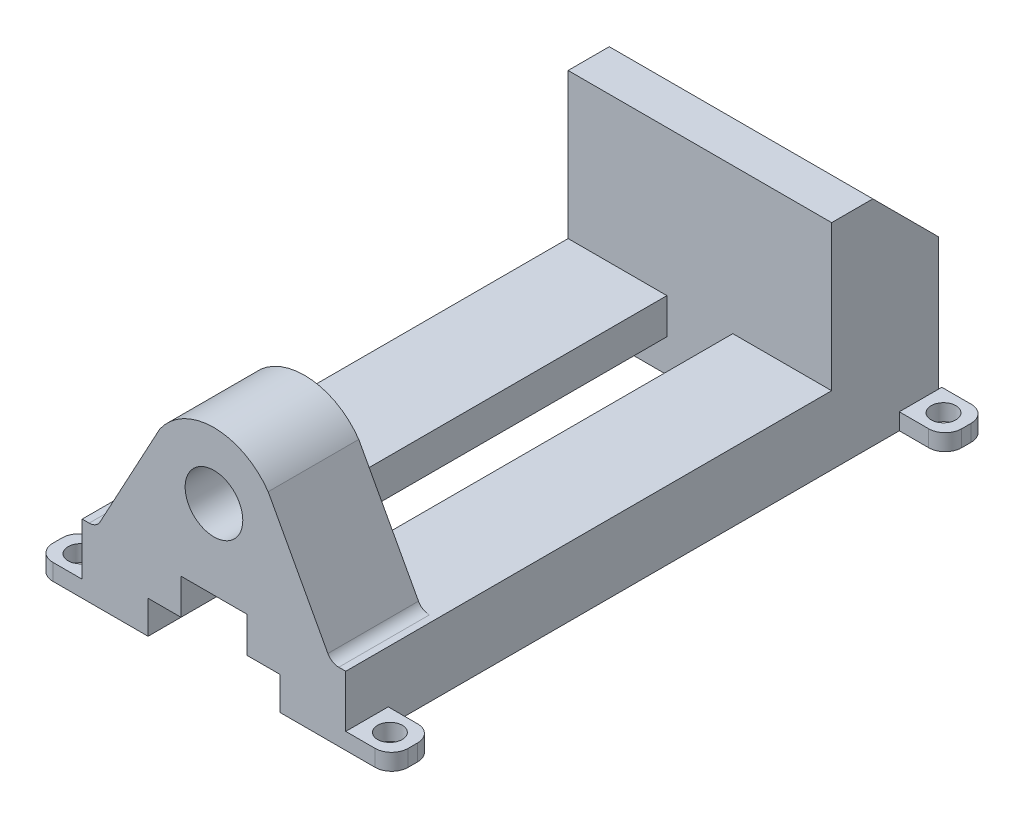
SolidWorks part; units mm, degrees
ref_plane "Front Plane" through (0, 0, 0) normal (0, 0, 1) x (1, 0, 0)
ref_plane "Top Plane" through (0, 0, 0) normal (0, 1, 0) x (1, 0, 0)
ref_plane "Right Plane" through (0, 0, 0) normal (1, 0, 0) x (0, 0, -1)
sketch "Sketch1" plane through (0, 0, 0) normal (0, 0, 1) x (1, 0, 0)
  line L0 (-31.5512, -18.1216) -> (32.4488, -18.1216)
  line L1 (-31.5512, -18.1216) -> (32.4488, -18.1216)
  line L2 (-31.5512, -18.1216) -> (-31.5512, -1.4716)
  line L3 (-31.5512, -1.4716) -> (-29.8548, -1.4716)
  line L4 (-27.2168, 0.0997) -> (-12.7169, 26.8735)
  line L5 (32.4488, -18.1216) -> (32.4488, -1.4716)
  line L6 (32.4488, -1.4716) -> (30.7525, -1.4716)
  line L7 (28.1145, 0.0997) -> (13.6146, 26.8735)
  arc A0 (15.2575, 23.8399) -> (-14.3598, 23.8399) centre (0.4488, 17.7816) ccw
  arc A1 (-29.8548, -1.4716) -> (-27.2168, 0.0997) centre (-29.8548, 1.5284) ccw
  arc A2 (30.7525, -1.4716) -> (28.1145, 0.0997) centre (30.7525, 1.5284) cw
  point P0 (0.4488, -0.17)
  point P1 (0.4488, -0.17)
  dimension "D3" = 3
  dimension "D1" = 64
  dimension "D2" = 16.65
extrude "Boss-Extrude1" add sketch "Sketch1" along normal blind 22 contours L6 A2 L7 A0 L4 A1 L3 L2 L0 L5
hole_wizard "M16 Tapped Hole1" positions "Sketch2" profile "Sketch3" tap size "M16" standard "ISO" end condition through all
sketch "Sketch2" plane through (0, 0, 22) normal (0, 0, 1) x (1, 0, 0)
  arc A0 (13.6146, 26.8735) -> (-12.7169, 26.8735) centre (0.4488, 17.7816) ccw construction
  point P0 (0.4488, 17.7816)
  dimension "D1" = 32
  dimension "D2" = 0
sketch "Sketch3" plane through (0.4488, 17.7816, 22) normal (1, 0, 0) x (0, -1, 0)
  line L0 (0, 0) -> (0, 22)
  line L1 (0, 22) -> (7, 22)
  line L2 (7, 22) -> (7, 0)
  line L5 (7, 0) -> (0, 0)
  line L11 (0, -6.35) -> (0, 107.95) construction
  dimension "Thru Tap Drill Dia." = 14
  dimension "Thru Tap Drill Depth" = 22
cosmetic thread "Hole Thread1" parameters "D2"=16
sketch "Sketch4" plane through (0, 0, 0) normal (0, 0, 1) x (1, 0, 0)
  line L1 (0.4488, -33.3057) -> (0.4488, 71.1608) construction
  line L7 (16.4488, -18.1216) -> (16.4488, -10.1216)
  line L8 (-31.5512, -18.1216) -> (32.4488, -18.1216) construction
  line L9 (16.4488, -10.1216) -> (8.4488, -10.1216)
  line L10 (8.4488, -10.1216) -> (8.4488, -1.4716)
  line L11 (8.4488, -1.4716) -> (32.4488, -1.4716)
  line L12 (32.4488, -18.1216) -> (32.4488, -1.4716) construction
  line L13 (32.4488, -1.4716) -> (32.4488, -18.1216)
  line L14 (32.4488, -18.1216) -> (16.4488, -18.1216)
  line L15 (-7.5512, -10.1216) -> (-7.5512, -1.4716)
  line L16 (-15.5512, -18.1216) -> (-15.5512, -10.1216)
  line L17 (-15.5512, -10.1216) -> (-7.5512, -10.1216)
  line L18 (-7.5512, -1.4716) -> (-31.5512, -1.4716)
  line L19 (-31.5512, -18.1216) -> (-15.5512, -18.1216)
  line L20 (-31.5512, -1.4716) -> (-31.5512, -18.1216)
  point P4 (0.4488, -18.1216)
  dimension "D1" = 16
  dimension "D2" = 16.65
  dimension "D3" = 8.65
  dimension "D4" = 8
extrude "Boss-Extrude2" add sketch "Sketch4" against normal blind 96
sketch "Sketch5" plane through (0, 0, 22) normal (0, 0, 1) x (1, 0, 0)
  line L9 (-15.5512, -18.1216) -> (16.4488, -18.1216)
  line L10 (-31.5512, -18.1216) -> (32.4488, -18.1216) construction
  line L11 (16.4488, -18.1216) -> (16.4488, -10.1216)
  line L12 (16.4488, -10.1216) -> (8.4488, -10.1216)
  line L13 (8.4488, -10.1216) -> (8.4488, -1.4716)
  line L14 (8.4488, -1.4716) -> (-7.5512, -1.4716)
  line L16 (-7.5512, -10.1216) -> (-7.5512, -1.4716)
  line L17 (-15.5512, -10.1216) -> (-7.5512, -10.1216)
  line L18 (-15.5512, -18.1216) -> (-15.5512, -10.1216)
  dimension "D2" = 8
  dimension "D3" = 8
  dimension "D4" = 8.65
extrude "Cut-Extrude1" cut sketch "Sketch5" against normal through all
sketch "Sketch8" plane through (0, 0, -96) normal (0, 0, -1) x (-1, 0, 0)
  line L1 (-32.4488, -18.1216) -> (31.5512, -18.1216)
  line L2 (-32.4488, -18.1216) -> (-32.4488, 33.8784)
  line L3 (-32.4488, 33.8784) -> (31.5512, 33.8784)
  line L4 (31.5512, -18.1216) -> (31.5512, 33.8784)
  dimension "D1" = 52
extrude "Boss-Extrude3" add sketch "Sketch8" along normal blind 26
chamfer "Chamfer1" distance 16 angle 45 1 edges at (0.4488, 33.8784, -122)
sketch "Sketch11" plane through (0, -18.1216, 0) normal (0, -1, 0) x (-1, 0, 0)
  line L1 (-32.4488, -22) -> (-39.5888, -22)
  line L2 (-32.4488, -22) -> (-32.4488, -11.68)
  line L3 (-32.4488, -11.68) -> (-39.5888, -11.68)
  line L4 (-43.5888, -18) -> (-43.5888, -15.68)
  line L5 (31.5512, -11.68) -> (38.6912, -11.68)
  line L6 (42.6912, -18) -> (42.6912, -15.68)
  line L7 (31.5512, -22) -> (38.6912, -22)
  line L8 (31.5512, -22) -> (31.5512, -11.68)
  line L9 (-32.4488, 112.435) -> (-39.5888, 112.435)
  line L10 (-43.5888, 118.755) -> (-43.5888, 116.435)
  line L11 (-32.4488, 122.755) -> (-39.5888, 122.755)
  line L12 (-32.4488, 122.755) -> (-32.4488, 112.435)
  line L13 (31.5512, 122.755) -> (31.5512, 112.435)
  line L14 (31.5512, 122.755) -> (38.6912, 122.755)
  line L15 (42.6912, 118.755) -> (42.6912, 116.435)
  line L16 (31.5512, 112.435) -> (38.6912, 112.435)
  circle A0 centre (-38.0188, -16.84) radius 3
  circle A1 centre (37.1212, -16.84) radius 3
  circle A2 centre (-38.0188, 117.595) radius 3
  circle A3 centre (37.1212, 117.595) radius 3
  arc A4 (-43.5888, 118.755) -> (-39.5888, 122.755) centre (-39.5888, 118.755) cw
  arc A5 (-39.5888, 112.435) -> (-43.5888, 116.435) centre (-39.5888, 116.435) cw
  arc A6 (42.6912, 116.435) -> (38.6912, 112.435) centre (38.6912, 116.435) cw
  arc A7 (42.6912, 118.755) -> (38.6912, 122.755) centre (38.6912, 118.755) ccw
  arc A8 (42.6912, -15.68) -> (38.6912, -11.68) centre (38.6912, -15.68) ccw
  arc A9 (38.6912, -22) -> (42.6912, -18) centre (38.6912, -18) ccw
  arc A10 (-43.5888, -15.68) -> (-39.5888, -11.68) centre (-39.5888, -15.68) cw
  arc A11 (-39.5888, -22) -> (-43.5888, -18) centre (-39.5888, -18) cw
  dimension "D3" = 4
extrude "Boss-Extrude4" add sketch "Sketch11" against normal blind 4
